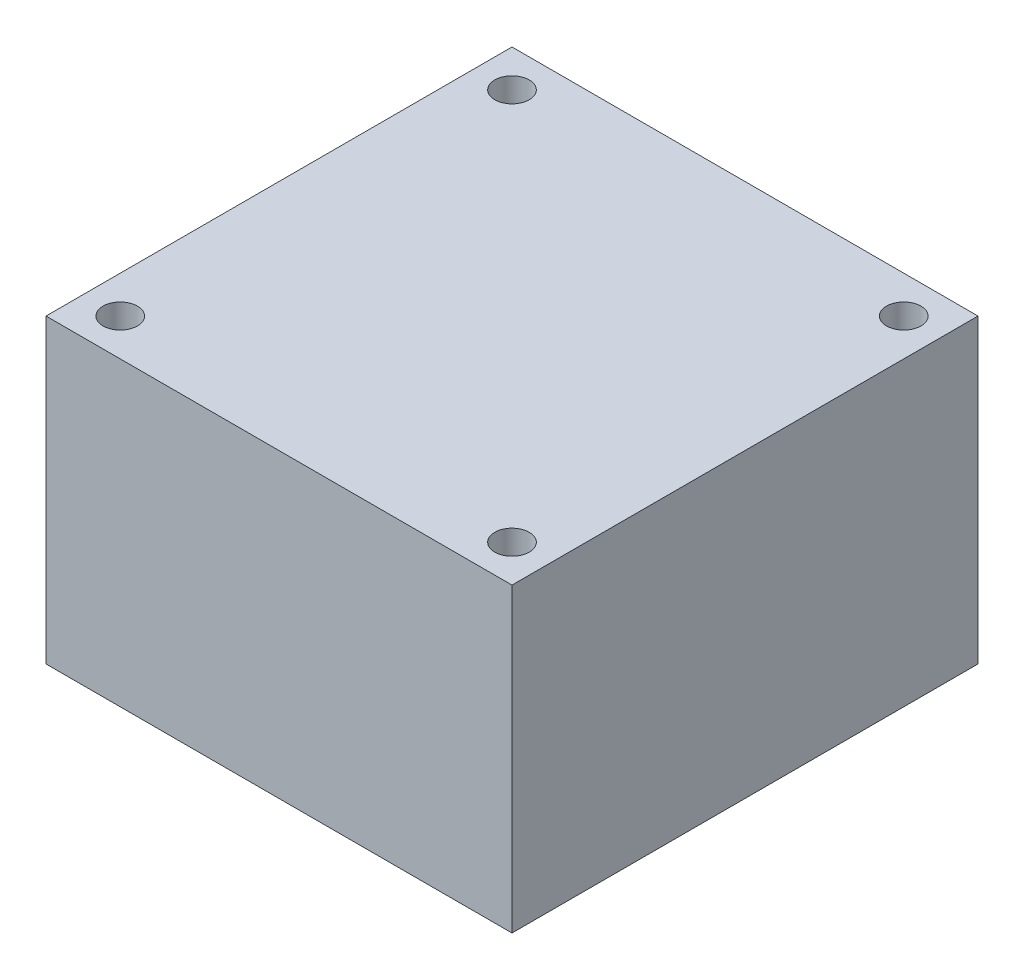
SolidWorks part; units mm, degrees
ref_plane "前视基准面" through (0, 0, 0) normal (0, 0, 1) x (1, 0, 0)
ref_plane "上视基准面" through (0, 0, 0) normal (0, 1, 0) x (1, 0, 0)
ref_plane "右视基准面" through (0, 0, 0) normal (1, 0, 0) x (0, 0, -1)
sketch "草图1" plane through (0, 0, 0) normal (0, 1, 0) x (1, 0, 0)
  line L0 (0, 21.65) -> (0, -21.65) construction
  line L1 (-21.65, 21.65) -> (21.65, 21.65)
  line L2 (-21.65, 21.65) -> (-21.65, -21.65)
  line L3 (-21.65, -21.65) -> (21.65, -21.65)
  line L4 (21.65, 21.65) -> (21.65, -21.65)
  line L5 (-21.65, 21.65) -> (21.65, -21.65) construction
  line L6 (-21.65, -21.65) -> (21.65, 21.65) construction
  line L7 (-18.2, 18.2) -> (18.2, 18.2) construction
  line L8 (-18.2, 18.2) -> (-18.2, -18.2) construction
  line L9 (-18.2, -18.2) -> (18.2, -18.2) construction
  line L10 (18.2, 18.2) -> (18.2, -18.2) construction
  line L11 (-18.2, 18.2) -> (18.2, -18.2) construction
  line L12 (-18.2, -18.2) -> (18.2, 18.2) construction
  line L13 (-21.65, 0) -> (21.65, 0) construction
  circle A0 centre (18.2, 18.2) radius 1.6
  circle A1 centre (-18.2, 18.2) radius 1.6
  circle A2 centre (18.2, -18.2) radius 1.6
  circle A3 centre (-18.2, -18.2) radius 1.6
  point P0 (0, 0)
  point P6 (0, 0)
  dimension "D4" = 3.2
  dimension "D1" = 43.3
  dimension "D2" = 43.3
  dimension "D3" = 36.4
extrude "凸台-拉伸1" add sketch "草图1" along normal blind 28
